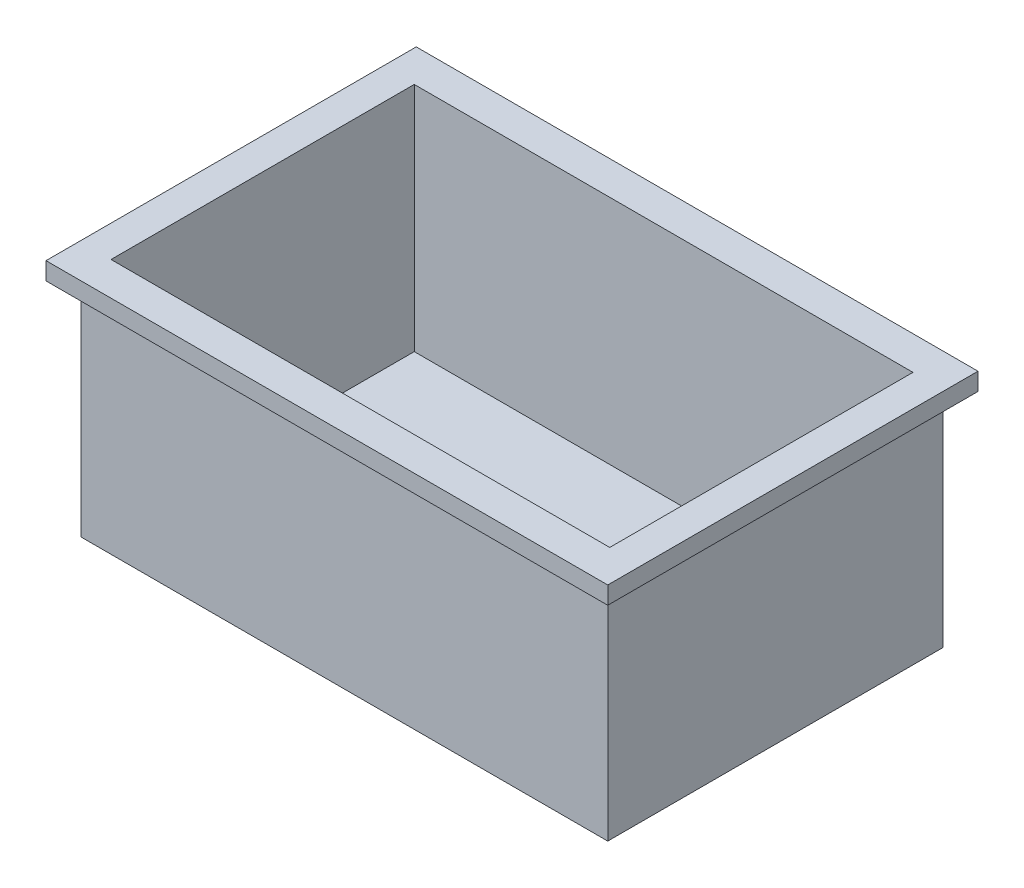
SolidWorks part; units mm, degrees
ref_plane "Front Plane" through (0, 0, 0) normal (0, 0, 1) x (1, 0, 0)
ref_plane "Top Plane" through (0, 0, 0) normal (0, 1, 0) x (1, 0, 0)
ref_plane "Right Plane" through (0, 0, 0) normal (1, 0, 0) x (0, 0, -1)
sketch "Sketch1" plane through (0, 0, 0) normal (0, 1, 0) x (1, 0, 0)
  line L1 (-330, 210) -> (330, 210)
  line L2 (-330, 210) -> (-330, -210)
  line L3 (-330, -210) -> (330, -210)
  line L4 (330, 210) -> (330, -210)
  line L5 (-330, 210) -> (330, -210) construction
  line L6 (-330, -210) -> (330, 210) construction
  line L7 (-312.5, -190) -> (312.5, -190)
  line L8 (-312.5, -190) -> (-312.5, 190)
  line L9 (-312.5, 190) -> (312.5, 190)
  line L10 (312.5, -190) -> (312.5, 190)
  line L11 (-312.5, -190) -> (312.5, 190) construction
  line L12 (-312.5, 190) -> (312.5, -190) construction
  point P0 (0, 0)
  point P6 (0, 0)
  dimension "D1" = 660
  dimension "D2" = 420
  dimension "D3" = 625
  dimension "D4" = 380
extrude "Boss-Extrude1" add sketch "Sketch1" along normal blind 300
sketch "Sketch2" plane through (0, 0, 0) normal (0, -1, 0) x (1, 0, 0)
  line L1 (312.5, 190) -> (-312.5, 190)
  line L2 (312.5, 190) -> (312.5, -190)
  line L3 (312.5, -190) -> (-312.5, -190)
  line L4 (-312.5, 190) -> (-312.5, -190)
extrude "Boss-Extrude2" add sketch "Sketch2" against normal blind 10 separate body
sketch "Sketch3" plane through (0, 300, 0) normal (0, 1, 0) x (1, 0, 0)
  line L0 (330, 210) -> (-330, 210) construction
  line L1 (352, -232) -> (-352, -232)
  line L2 (352, -232) -> (352, 232)
  line L3 (352, 232) -> (-352, 232)
  line L4 (-352, -232) -> (-352, 232)
  line L5 (-330, -210) -> (330, -210) construction
  line L6 (-330, 210) -> (-330, -210) construction
  line L7 (330, -210) -> (330, 210) construction
  line L9 (330, -210) -> (-330, -210)
  line L10 (330, -210) -> (330, 210)
  line L11 (330, 210) -> (-330, 210)
  line L12 (-330, -210) -> (-330, 210)
  dimension "D1" = 22
  dimension "D2" = 22
  dimension "D3" = 22
  dimension "D4" = 22
extrude "Boss-Extrude3" add sketch "Sketch3" against normal blind 22
equation "\"Tank_Width\" = 660mm"
equation "\"Tank_Depth\" = 420mm"
equation "\"Tank_Height\" = 300mm"
equation "\"D1@Sketch1\"=\"Tank_Width\""
equation "\"D2@Sketch1\"=\"Tank_Depth\""
equation "\"D1@Boss-Extrude1\"=\"Tank_Height\""
